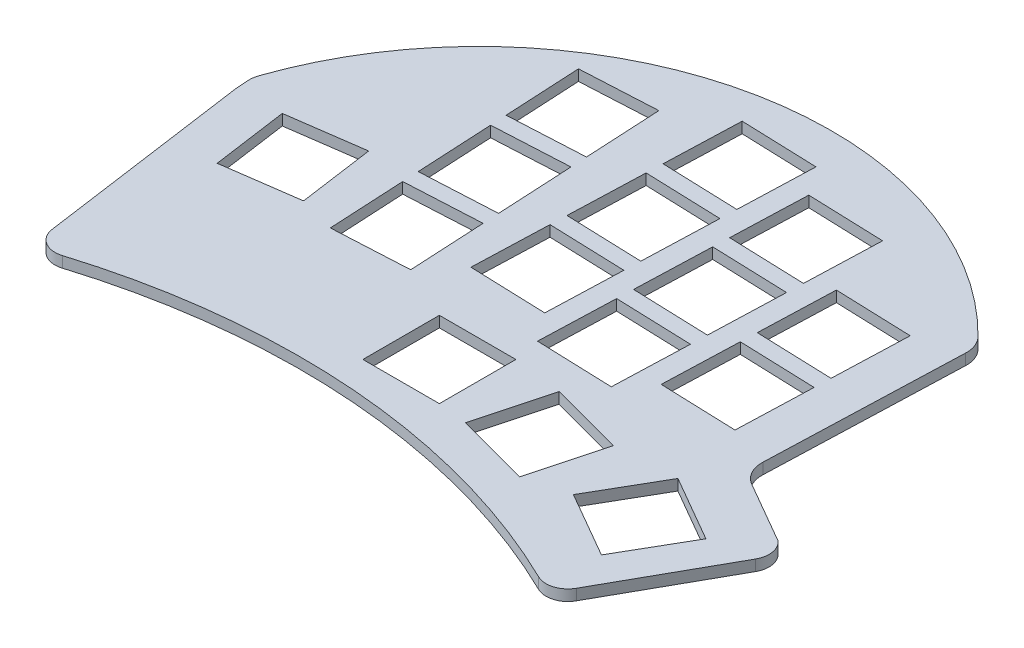
SolidWorks part; units mm, degrees
ref_plane "Front Plane" through (0, 0, 0) normal (0, 0, 1) x (1, 0, 0)
ref_plane "Top Plane" through (0, 0, 0) normal (0, 1, 0) x (1, 0, 0)
ref_plane "Right Plane" through (0, 0, 0) normal (1, 0, 0) x (0, 0, -1)
sketch "Sketch1" plane through (0, 0, 0) normal (0, 1, 0) x (1, 0, 0)
  line L0 (-10.587, 42.3833) -> (-5.0463, 2.9591)
  line L1 (99.7777, -5.7003) -> (111.5501, 15.3543)
  line L2 (110.7654, 20.2516) -> (96.7654, 28.3345)
  line L3 (96.7654, 28.3345) -> (98.197, 69.3287)
  line L4 (-10.8145, 45.5661) -> (-10.587, 42.3833)
  arc A0 (-5.0463, 2.9591) -> (0, 0) centre (-1.1683, 3.79) ccw
  arc A1 (0, 0) -> (94.542, -7.3478) centre (37.9806, -123.2108) cw
  arc A2 (94.542, -7.3478) -> (99.7777, -5.7003) centre (96.2914, -3.7642) ccw
  arc A3 (111.5501, 15.3543) -> (110.7654, 20.2516) centre (108.0588, 17.3064) ccw
  arc A4 (98.197, 69.3287) -> (-10.8145, 45.5661) centre (50.6496, 25.5254) ccw
  point P16 (0, 0)
  line B0 (-13.8416, 45.0456) -> (-13.4373, 42.1685)
  line B1 (-5.0463, 2.9591) -> (-13.3874, 41.8872)
  line B2 (111.5501, 15.3543) -> (99.7777, -5.7003)
  line B3 (97.906, 32.0639) -> (110.7647, 20.2522)
  line B4 (96.9062, 69.3752) -> (97.906, 32.0639)
  line B5 (-0.4496, 28.7944) -> (13.4142, 30.7429)
  line B6 (13.4142, 30.7429) -> (11.4658, 44.6066)
  line B7 (11.4658, 44.6066) -> (-2.398, 42.6582)
  line B8 (-2.398, 42.6582) -> (-0.4496, 28.7944)
  line B9 (20.1529, 28.8995) -> (34.1337, 29.6322)
  line B10 (34.1337, 29.6322) -> (33.401, 43.613)
  line B11 (33.401, 43.613) -> (19.4202, 42.8803)
  line B12 (19.4202, 42.8803) -> (20.1529, 28.8995)
  line B13 (19.2632, 45.8762) -> (33.244, 46.6089)
  line B14 (33.244, 46.6089) -> (32.5113, 60.5897)
  line B15 (32.5113, 60.5897) -> (18.5305, 59.857)
  line B16 (18.5305, 59.857) -> (19.2632, 45.8762)
  line B17 (18.3734, 62.8529) -> (32.3543, 63.5856)
  line B18 (32.3543, 63.5856) -> (31.6216, 77.5664)
  line B19 (31.6216, 77.5664) -> (17.6407, 76.8337)
  line B20 (17.6407, 76.8337) -> (18.3734, 62.8529)
  line B21 (39.2478, 35.5447) -> (53.2393, 35.0561)
  line B22 (53.2393, 35.0561) -> (53.7279, 49.0476)
  line B23 (53.7279, 49.0476) -> (39.7364, 49.5361)
  line B24 (39.7364, 49.5361) -> (39.2478, 35.5447)
  line B25 (39.8411, 52.5343) -> (53.8326, 52.0457)
  line B26 (53.8326, 52.0457) -> (54.3212, 66.0372)
  line B27 (54.3212, 66.0372) -> (40.3297, 66.5258)
  line B28 (40.3297, 66.5258) -> (39.8411, 52.5343)
  line B29 (40.4344, 69.524) -> (54.4259, 69.0354)
  line B30 (54.4259, 69.0354) -> (54.9144, 83.0268)
  line B31 (54.9144, 83.0268) -> (40.923, 83.5154)
  line B32 (40.923, 83.5154) -> (40.4344, 69.524)
  line B33 (57.0623, 29.9195) -> (71.0538, 29.4309)
  line B34 (71.0538, 29.4309) -> (71.5424, 43.4224)
  line B35 (71.5424, 43.4224) -> (57.5509, 43.911)
  line B36 (57.5509, 43.911) -> (57.0623, 29.9195)
  line B37 (57.6556, 46.9092) -> (71.6471, 46.4206)
  line B38 (71.6471, 46.4206) -> (72.1357, 60.4121)
  line B39 (72.1357, 60.4121) -> (58.1442, 60.9006)
  line B40 (58.1442, 60.9006) -> (57.6556, 46.9092)
  line B41 (58.2489, 63.8988) -> (72.2404, 63.4102)
  line B42 (72.2404, 63.4102) -> (72.729, 77.4017)
  line B43 (72.729, 77.4017) -> (58.7375, 77.8903)
  line B44 (58.7375, 77.8903) -> (58.2489, 63.8988)
  line B45 (75.2294, 34.3882) -> (89.2208, 33.8996)
  line B46 (89.2208, 33.8996) -> (89.7094, 47.8911)
  line B47 (89.7094, 47.8911) -> (75.718, 48.3797)
  line B48 (75.718, 48.3797) -> (75.2294, 34.3882)
  line B49 (75.8227, 51.3779) -> (89.8141, 50.8893)
  line B50 (89.8141, 50.8893) -> (90.3027, 64.8808)
  line B51 (90.3027, 64.8808) -> (76.3112, 65.3693)
  line B52 (76.3112, 65.3693) -> (75.8227, 51.3779)
  line B53 (43.9813, 11.0336) -> (57.9813, 11.0336)
  line B54 (57.9813, 11.0336) -> (57.9813, 25.0336)
  line B55 (57.9813, 25.0336) -> (43.9813, 25.0336)
  line B56 (43.9813, 25.0336) -> (43.9813, 11.0336)
  line B57 (63.4081, 10.3839) -> (76.931, 6.7604)
  line B58 (76.931, 6.7604) -> (80.5545, 20.2834)
  line B59 (80.5545, 20.2834) -> (67.0315, 23.9068)
  line B60 (67.0315, 23.9068) -> (63.4081, 10.3839)
  line B61 (96.7944, 1.8799) -> (103.7944, 14.0042)
  line B62 (103.7944, 14.0042) -> (91.6701, 21.0042)
  line B63 (91.6701, 21.0042) -> (84.6701, 8.8799)
  line B64 (84.6701, 8.8799) -> (96.7944, 1.8799)
  arc B65 (95.827, 72.0025) -> (-13.7017, 46.7848) centre (48.3898, 27.5692) ccw
  arc B66 (-13.7017, 46.7848) -> (-13.8416, 45.0456) centre (-9.8805, 45.6023) ccw
  arc B67 (-13.4373, 42.1685) -> (-13.3874, 41.8872) centre (-9.4762, 42.7252) ccw
  arc B68 (-5.0461, 2.9585) -> (0.0344, -0.0287) centre (-1.1349, 3.7965) ccw
  arc B69 (94.542, -7.3478) -> (0.0344, -0.0287) centre (37.9628, -124.1034) ccw
  arc B70 (94.5428, -7.3482) -> (99.7777, -5.7003) centre (96.2864, -3.7482) ccw
  arc B71 (111.5501, 15.3543) -> (110.7654, 20.2516) centre (108.0588, 17.3064) ccw
  arc B72 (96.9062, 69.3761) -> (95.827, 72.0025) centre (92.9076, 69.268) ccw
  dimension "D1" = 0
  dimension "D2" = 0
  dimension "D3" = 0
  dimension "D4" = 14
sketch_block_instance "switch_plate (1)-1"
sketch_block "switch_plate (1)"
extrude "Boss-Extrude1" add sketch "Sketch1" along normal blind 2 contours B7 B8 B5 B6 | B11 B12 B9 B10 | B15 B16 B13 B14 | B19 B20 B17 B18 | B31 B32 B29 B30 | B27 B28 B25 B26 | B23 B24 B21 B22 | B55 B56 B53 B54 | B59 B60 B57 B58 | B63 B64 B61 B62 | B47 B48 B45 B46 | B35 B36 B33 B34 | B39 B40 B37 B38 | B43 B44 B41 B42 | B51 B52 B49 B50 | A4 L4 L0 A0 A1 A2 L1 A3 L2 L3
fillet "Fillet1" radius 5 3 edges at (98.197, 1, -69.3287) (-10.8145, 1, -45.5661) (96.7654, 1, -28.3345)
